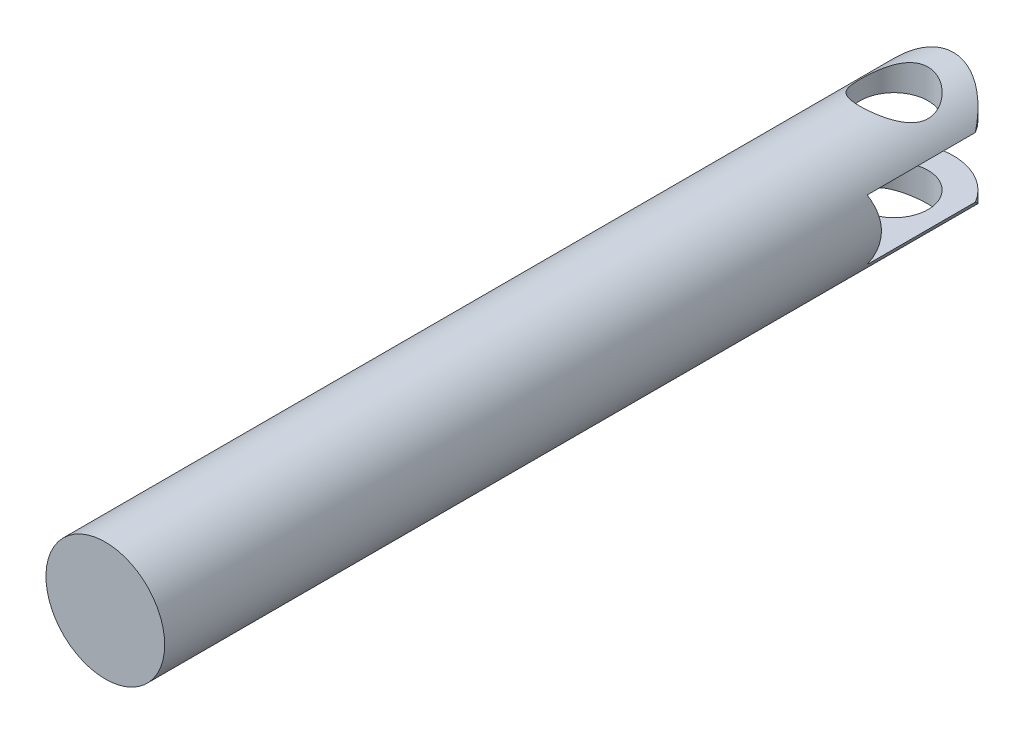
SolidWorks part; units mm, degrees
ref_plane "前视基准面" through (0, 0, 0) normal (0, 0, 1) x (1, 0, 0)
ref_plane "上视基准面" through (0, 0, 0) normal (0, 1, 0) x (1, 0, 0)
ref_plane "右视基准面" through (0, 0, 0) normal (1, 0, 0) x (0, 0, -1)
sketch "草图2" plane through (0, 0, 0) normal (0, 0, 1) x (1, 0, 0)
  circle A0 centre (0, 0) radius 7
extrude "凸台-拉伸1" add sketch "草图2" along normal blind 100
sketch "草图3" plane through (0, 0, 0) normal (0, 1, 0) x (1, 0, 0)
  line L0 (0, -7) -> (17.5301, -7)
  line L1 (17.5301, -7) -> (-17.5301, -7)
  circle A0 centre (0, -7) radius 7
  circle A1 centre (0, -7) radius 17.5301
extrude "切除-拉伸3" cut sketch "草图3" against normal mid plane 16 contours L1 A1 A0
sketch "草图5" plane through (0, 0, 0) normal (0, 1, 0) x (1, 0, 0)
  circle A0 centre (0, -7) radius 4.01
  point P2 (0, 0)
  point P3 (0, 0)
sketch "草图6" plane through (0, 0, 0) normal (0, 1, 0) x (1, 0, 0)
  circle A0 centre (0, -7) radius 11
extrude "切除-拉伸5" cut sketch "草图6" against normal mid plane 7.1
extrude "切除-拉伸6" cut sketch "草图5" against normal mid plane 160
